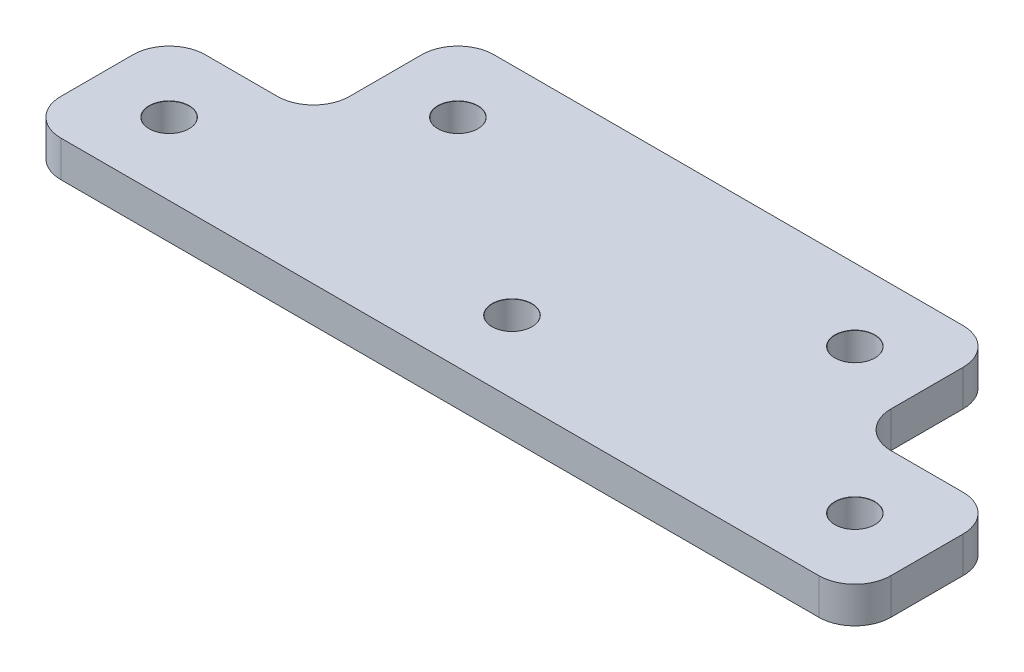
SolidWorks part; units mm, degrees
ref_plane "Front Plane" through (0, 0, 0) normal (0, 0, 1) x (1, 0, 0)
ref_plane "Top Plane" through (0, 0, 0) normal (0, 1, 0) x (1, 0, 0)
ref_plane "Right Plane" through (0, 0, 0) normal (1, 0, 0) x (0, 0, -1)
sketch "Sketch2" plane through (0, 0, 0) normal (0, 1, 0) x (1, 0, 0)
  line L0 (-57.5, 0) -> (57.5, 0)
  line L1 (-55, 0) -> (55, 0) construction
  line L2 (57.5, 0) -> (57.5, 20)
  line L3 (57.5, 20) -> (37.5, 20)
  line L4 (37.5, 20) -> (37.5, 40)
  line L5 (37.5, 40) -> (-37.5, 40)
  line L6 (-37.5, 40) -> (-37.5, 20)
  line L7 (-37.5, 20) -> (-57.5, 20)
  line L8 (-57.5, 20) -> (-57.5, 0)
  line L9 (0, -55) -> (0, 55) construction
  point P6 (0, 0)
  point P12 (0, 40)
  dimension "D1" = 75
  dimension "D2" = 20
  dimension "D3" = 20
  dimension "D4" = 20
extrude "Boss-Extrude1" add sketch "Sketch2" along normal blind 5
fillet "Fillet2" radius 5 8 edges at (37.5, 2.5, -20) (-37.5, 2.5, -20) (-37.5, 2.5, -40) (37.5, 2.5, -40) (57.5, 2.5, 0) (57.5, 2.5, -20) (-57.5, 2.5, -20) (-57.5, 2.5, 0)
sketch "Sketch4" plane through (0, 5, 0) normal (0, 1, 0) x (1, 0, 0)
  line L0 (-37.5, 30) -> (-27.5, 30) construction
  line L1 (-37.5, 35) -> (-37.5, 25) construction
  line L2 (32.5, 40) -> (-32.5, 40) construction
  line L3 (-37.5, 30) -> (-27.5, 30) construction
  line L4 (-42.5, 20) -> (-52.5, 20) construction
  dimension "D1" = 10
  dimension "D2" = 10
  dimension "D3" = 10
hole_wizard "M5 Clearance Hole1" positions "3DSketch1" profile "Sketch5" hole size "M5" standard "ANSI Metric" end condition through all
sketch3d "3DSketch1"
  point P0 (-27.5, 5, -30)
  point P3 (-27.5, 5, -30)
sketch "Sketch5" plane through (-27.5, 5, -30) normal (1, 0, 0) x (0, 0, 1)
  line L0 (0, 0) -> (0, 5)
  line L1 (0, 5) -> (2.75, 5)
  line L2 (2.75, 5) -> (2.75, 0.025)
  line L3 (2.75, 0.025) -> (2.775, 0)
  line L5 (2.775, 0) -> (0, 0)
  line L6 (-2.75, 0.025) -> (-2.775, 0) construction
  line L11 (0, -6.35) -> (0, 107.95) construction
  dimension "Thru Hole Dia." = 5.5
  dimension "Thru Hole Depth" = 5
  dimension "Near C'Sink Dia." = 5.55
  dimension "Near C'Sink Angle" = 90
mirror "Mirror1" about plane through (0, 0, 0) normal (1, 0, 0) of "M5 Clearance Hole1"
sketch "Sketch7" plane through (0, 5, 0) normal (0, 1, 0) x (1, 0, 0)
  line L0 (-57.5, 10) -> (-47.5, 10) construction
  line L1 (-57.5, 15) -> (-57.5, 5) construction
  dimension "D1" = 10
hole_wizard "M5 Clearance Hole2" positions "3DSketch3" profile "Sketch8" hole size "M5" standard "ANSI Metric" end condition through all
sketch3d "3DSketch3"
  point P0 (-47.5, 5, -10)
sketch "Sketch8" plane through (-47.5, 5, -10) normal (1, 0, 0) x (0, 0, 1)
  line L0 (0, 0) -> (0, 5)
  line L1 (0, 5) -> (2.75, 5)
  line L2 (2.75, 5) -> (2.75, 0.025)
  line L3 (2.75, 0.025) -> (2.775, 0)
  line L5 (2.775, 0) -> (0, 0)
  line L6 (-2.75, 0.025) -> (-2.775, 0) construction
  line L11 (0, -6.35) -> (0, 107.95) construction
  dimension "Thru Hole Dia." = 5.5
  dimension "Thru Hole Depth" = 5
  dimension "Near C'Sink Dia." = 5.55
  dimension "Near C'Sink Angle" = 90
mirror "Mirror2" about plane through (0, 0, 0) normal (1, 0, 0) of "M5 Clearance Hole2"
sketch "Sketch9" plane through (0, 5, 0) normal (0, 1, 0) x (1, 0, 0)
  line L0 (0, 0) -> (0, 10) construction
  line L1 (0, -2.75) -> (0, 2.75) construction
  dimension "D1" = 10
hole_wizard "M5 Clearance Hole3" positions "3DSketch4" profile "Sketch10" hole size "M5" standard "ANSI Metric" end condition through all
sketch3d "3DSketch4"
  point P0 (0, 5, -10)
sketch "Sketch10" plane through (0, 5, -10) normal (1, 0, 0) x (0, 0, 1)
  line L0 (0, 0) -> (0, 5)
  line L1 (0, 5) -> (2.75, 5)
  line L2 (2.75, 5) -> (2.75, 0.025)
  line L3 (2.75, 0.025) -> (2.775, 0)
  line L5 (2.775, 0) -> (0, 0)
  line L6 (-2.75, 0.025) -> (-2.775, 0) construction
  line L11 (0, -6.35) -> (0, 107.95) construction
  dimension "Thru Hole Dia." = 5.5
  dimension "Thru Hole Depth" = 5
  dimension "Near C'Sink Dia." = 5.55
  dimension "Near C'Sink Angle" = 90
